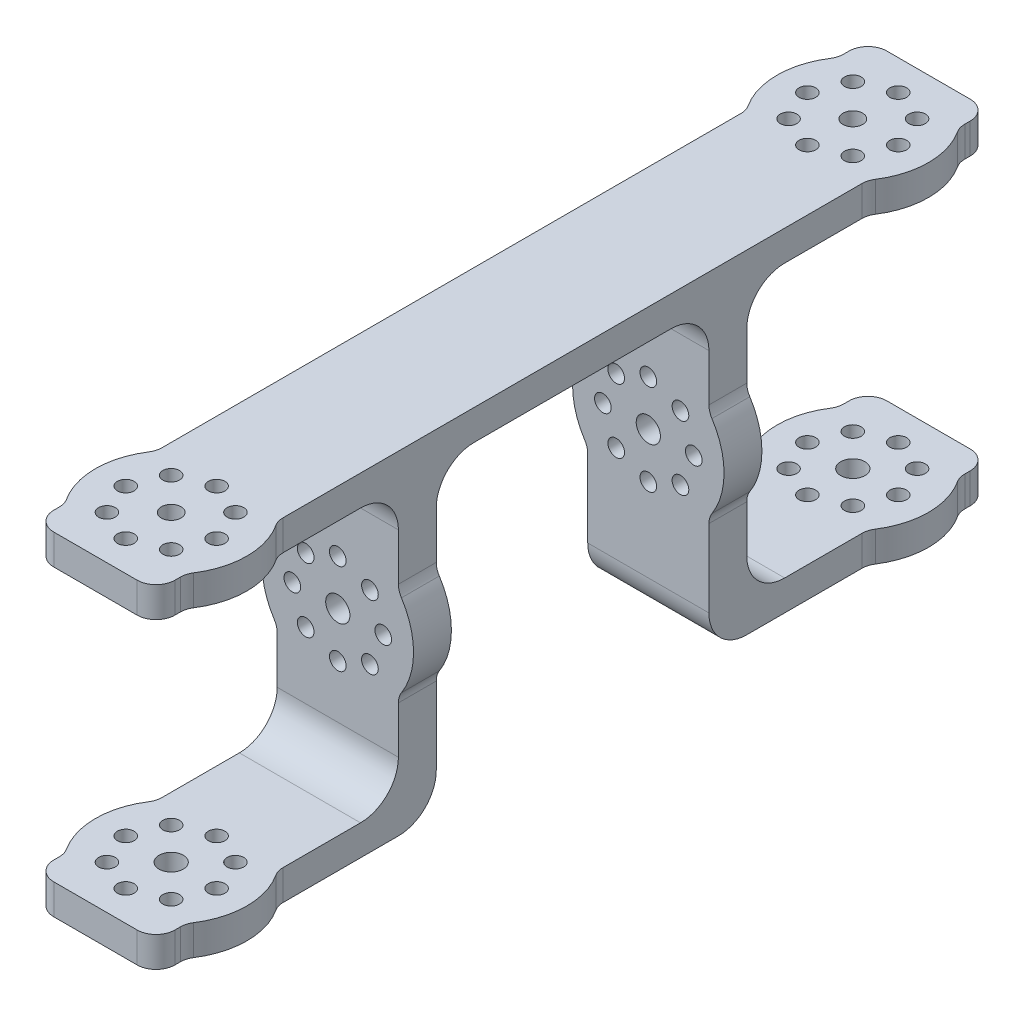
SolidWorks part; units mm, degrees
material "ABS"
ref_plane "正面" through (0, 0, 0) normal (0, 0, 1) x (1, 0, 0)
ref_plane "平面" through (0, 0, 0) normal (0, 1, 0) x (1, 0, 0)
ref_plane "右側面" through (0, 0, 0) normal (1, 0, 0) x (0, 0, -1)
sketch "ｽｹｯﾁ1" plane through (0, 0, 0) normal (0, 0, 1) x (1, 0, 0)
  line L0 (0, 0) -> (0, 36) construction
  line L1 (-8, 0) -> (8, 0)
  line L2 (-8, 0) -> (-8, 12)
  line L3 (-8, 36) -> (8, 36)
  line L4 (8, 0) -> (8, 12)
  line L5 (-8, 24) -> (-8, 36)
  line L6 (8, 24) -> (8, 36)
  circle A0 centre (0, 18) radius 6 construction
  circle A1 centre (0, 18) radius 1.6
  circle A2 centre (0, 24) radius 1.1
  circle A3 centre (4.2426, 22.2426) radius 1.1
  circle A4 centre (6, 18) radius 1.1
  circle A5 centre (4.2426, 13.7574) radius 1.1
  circle A6 centre (0, 12) radius 1.1
  circle A7 centre (-4.2426, 13.7574) radius 1.1
  circle A8 centre (-6, 18) radius 1.1
  circle A9 centre (-4.2426, 22.2426) radius 1.1
  arc A10 (-8, 24) -> (-8, 12) centre (0, 18) ccw
  arc A11 (8, 12) -> (8, 24) centre (0, 18) ccw
  point P29 (0, 18)
  dimension "D3" = 3.2
  dimension "D4" = 12
  dimension "D5" = 2.2
  dimension "D7" = 20
  dimension "D1" = 16
  dimension "D2" = 36
  dimension "D6" = 8
extrude "ﾎﾞｽ - 押し出し1" add sketch "ｽｹｯﾁ1" along normal blind 5
sketch "ｽｹｯﾁ2" plane through (0, 0, 0) normal (0, -1, 0) x (1, 0, 0)
  line L0 (8, 5) -> (8, 0) construction
  line L1 (-8, 0) -> (8, 0)
  line L2 (-8, 0) -> (-8, 21)
  line L3 (-8, 37) -> (8, 37)
  line L4 (8, 0) -> (8, 21)
  line L5 (0, 37) -> (0, 0) construction
  line L6 (-8, 33) -> (-8, 37)
  line L7 (8, 33) -> (8, 37)
  circle A0 centre (0, 27) radius 1.6
  circle A1 centre (0, 27) radius 6 construction
  circle A2 centre (6, 27) radius 1.1
  circle A3 centre (4.2426, 22.7574) radius 1.1
  circle A4 centre (0, 21) radius 1.1
  circle A5 centre (-4.2426, 22.7574) radius 1.1
  circle A6 centre (-6, 27) radius 1.1
  circle A7 centre (-4.2426, 31.2426) radius 1.1
  circle A8 centre (0, 33) radius 1.1
  circle A9 centre (4.2426, 31.2426) radius 1.1
  arc A10 (-8, 33) -> (-8, 21) centre (0, 27) ccw
  arc A11 (8, 21) -> (8, 33) centre (0, 27) ccw
  point P32 (0, 27)
  dimension "D2" = 12
  dimension "D3" = 3.2
  dimension "D5" = 2.2
  dimension "D7" = 10
  dimension "D1" = 37
  dimension "D4" = 10
  dimension "D6" = 8
extrude "ﾎﾞｽ - 押し出し2" add sketch "ｽｹｯﾁ2" along normal blind 4
sketch "ｽｹｯﾁ3" plane through (0, 36, 0) normal (0, 1, 0) x (1, 0, 0)
  line L0 (8, -5) -> (8, 0)
  line L1 (8, 0) -> (-8, 0)
  line L2 (-8, 0) -> (-8, -5)
  line L6 (8, -5) -> (-8, -5)
  line L7 (-8, -5) -> (-8, -21)
  line L8 (-8, -33) -> (-8, -37)
  line L9 (-8, -37) -> (8, -37)
  line L10 (8, -37) -> (8, -33)
  line L11 (8, -21) -> (8, -5)
  line L13 (-8, -5) -> (-8, -21)
  line L14 (-8, -33) -> (-8, -37)
  line L15 (-8, -37) -> (8, -37)
  line L16 (8, -37) -> (8, -33)
  line L17 (8, -21) -> (8, -5)
  circle A0 centre (4.2426, -22.7574) radius 1.1 construction
  circle A1 centre (0, -21) radius 1.1 construction
  arc A2 (-8, -21) -> (-8, -33) centre (0, -27) ccw
  arc A3 (8, -33) -> (8, -21) centre (0, -27) ccw
  arc A4 (-8, -21) -> (-8, -33) centre (0, -27) ccw
  arc A5 (8, -33) -> (8, -21) centre (0, -27) ccw
  circle A6 centre (-4.2426, -22.7574) radius 1.1 construction
  circle A7 centre (-6, -27) radius 1.1 construction
  circle A8 centre (-4.2426, -31.2426) radius 1.1 construction
  circle A9 centre (0, -33) radius 1.1 construction
  circle A10 centre (4.2426, -31.2426) radius 1.1 construction
  circle A11 centre (6, -27) radius 1.1 construction
  circle A12 centre (4.2426, -22.7574) radius 1.1
  circle A13 centre (0, -21) radius 1.1
  circle A14 centre (-4.2426, -22.7574) radius 1.1
  circle A15 centre (-6, -27) radius 1.1
  circle A16 centre (-4.2426, -31.2426) radius 1.1
  circle A17 centre (0, -33) radius 1.1
  circle A18 centre (4.2426, -31.2426) radius 1.1
  circle A19 centre (6, -27) radius 1.1
  circle A20 centre (0, -27) radius 1.3
  dimension "D2" = 2.6
  dimension "D1" = 0
extrude "ﾎﾞｽ - 押し出し3" add sketch "ｽｹｯﾁ3" along normal blind 4
fillet "ﾌｨﾚｯﾄ2" radius 2.5 16 edges at (8, 24, 2.5) (8, 12, 2.5) (8, 38, 21) (8, 38, 33) (8, 38, 37) (-8, 38, 37) (-8, 38, 33) (-8, 38, 21) (-8, 12, 2.5) (-8, 24, 2.5) (-8, -2, 21) (-8, -2, 33) (-8, -2, 37) (8, -2, 37) (8, -2, 21) (8, -2, 33)
ref_plane "平面1" through (0, 0, -18) normal (0, 0, 1) x (1, 0, 0)
mirror "ﾐﾗｰ2" about plane through (0, 0, -18) normal (0, 0, 1) of bodies 103
sketch "ｽｹｯﾁ4" plane through (0, 40, 0) normal (0, 1, 0) x (1, 0, 0)
  line L0 (-7.1, -5) -> (-4.9, -5) construction
  line L1 (-8, -5) -> (8, -5)
  line L2 (-8, -5) -> (-8, 41)
  line L3 (-8, 41) -> (8, 41)
  line L4 (8, -5) -> (8, 41)
  line L5 (-8, -5) -> (-8, -20.2177) construction
  line L6 (8, 56.2177) -> (8, 36) construction
  line L7 (-4.9, 41) -> (-7.1, 41) construction
  point P4 (0, 0)
  point P11 (0, 0)
  point P12 (8, 41.4351)
extrude "ﾎﾞｽ - 押し出し4" add sketch "ｽｹｯﾁ4" against normal up to surface (4 mm away) up to face at (0, 36, 26.4311)
fillet "ﾌｨﾚｯﾄ3" radius 5 8 edges at (0, 0, -41) (0, 36, -41) (0, -4, -36) (0, 36, -36) (0, 36, 0) (0, -4, 0) (0, 0, 5) (0, 36, 5)
